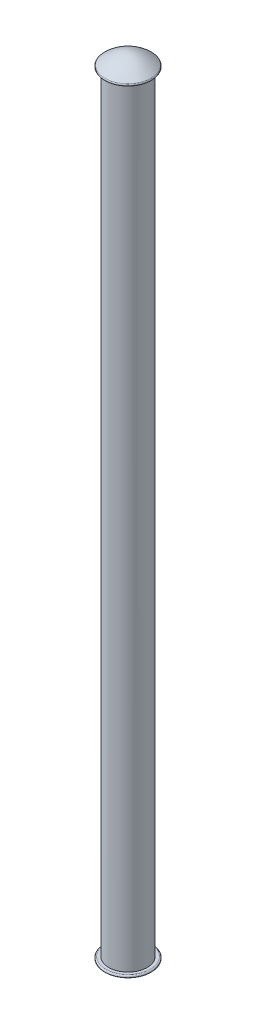
SolidWorks part; units mm, degrees
material "Chrome Stainless Steel"
ref_plane "Front Plane" through (0, 0, 0) normal (0, 0, 1) x (1, 0, 0)
ref_plane "Top Plane" through (0, 0, 0) normal (0, 1, 0) x (1, 0, 0)
ref_plane "Right Plane" through (0, 0, 0) normal (1, 0, 0) x (0, 0, -1)
sketch "Sketch1" plane through (0, 0, 0) normal (0, 1, 0) x (1, 0, 0)
  circle A0 centre (0, 0) radius 1.5
  dimension "D1" = 3
extrude "Boss-Extrude1" add sketch "Sketch1" along normal mid plane 60
sketch "Sketch2" plane through (0, 0, 0) normal (0, 0, 1) x (1, 0, 0)
  line L0 (0, 0) -> (0, 31) construction
  line L1 (0, 30) -> (-1.7315, 30)
  line L2 (1.5, 30) -> (-1.5, 30) construction
  line L3 (0, 31) -> (0, 30)
  line L4 (0.7895, 31) -> (-0.7895, 31) construction
  arc A1 (-1.7315, 30) -> (-1.7943, 30.1778) centre (-1.7315, 30.1) cw
  spline S0 degree 3 poles (-1.7943, 30.1778) (-1.297, 30.5792) (-0.6579, 31) (0, 31) knots 0 0 0 0 1 1 1 1
  point P12 (-2, 30)
  dimension "D3" = 0.1
  dimension "D4" = 0.1778
  dimension "D1" = 1
  dimension "D2" = 2
  dimension "D5" = 1.7943
revolve "Revolve1" add sketch "Sketch2" angle 360 about L3
mirror "Mirror1" about plane through (0, 0, 0) normal (0, 1, 0) of "Revolve1"
